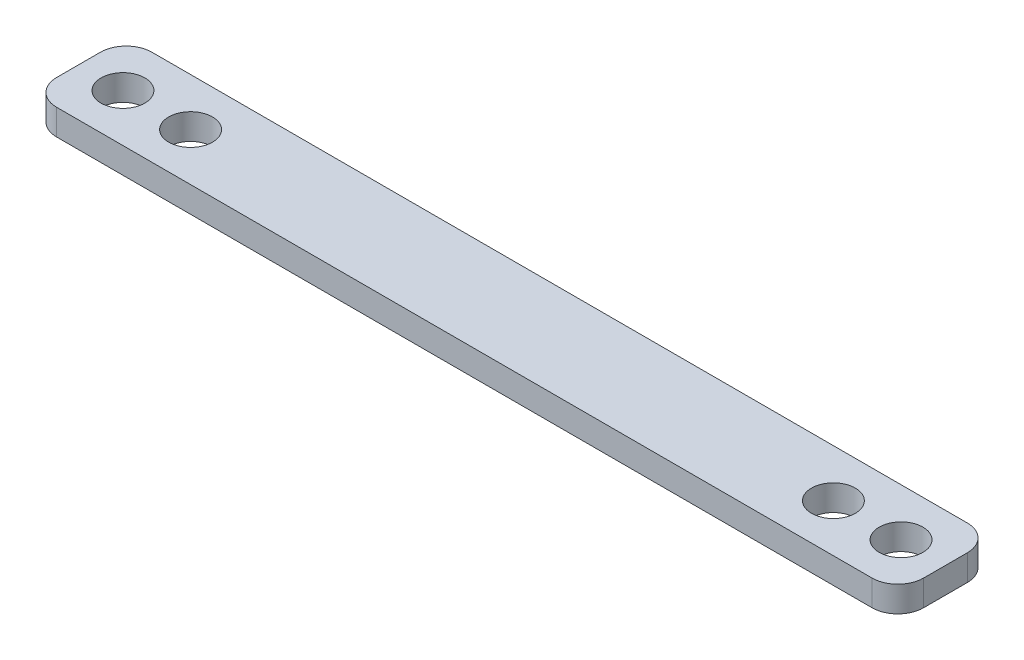
SolidWorks part; units mm, degrees
ref_plane "前视基准面" through (0, 0, 0) normal (0, 0, 1) x (1, 0, 0)
ref_plane "上视基准面" through (0, 0, 0) normal (0, 1, 0) x (1, 0, 0)
ref_plane "右视基准面" through (0, 0, 0) normal (1, 0, 0) x (0, 0, -1)
other "Configuration Table"
sketch "草图1" plane through (0, 0, 0) normal (0, 1, 0) x (1, 0, 0)
  line L0 (0.1939, -0.2441) -> (0.1939, 8.5567) construction
  line L5 (0.1939, 1.1668) -> (-30.0061, 1.1668)
  line L6 (33.8439, 4.8668) -> (-33.4561, 4.8668)
  line L8 (33.8439, 4.8668) -> (33.8439, -2.5332)
  line L9 (33.8439, -2.5332) -> (-33.4561, -2.5332)
  line L10 (-33.4561, 4.8668) -> (-33.4561, -2.5332)
  line L11 (33.8439, 4.8668) -> (-33.4561, -2.5332) construction
  line L12 (33.8439, -2.5332) -> (-33.4561, 4.8668) construction
  circle A2 centre (-24.7561, 1.1668) radius 1.7
  circle A3 centre (25.1439, 1.1668) radius 1.7
  circle A4 centre (-30.0061, 1.1668) radius 1.7
  circle A5 centre (30.3939, 1.1668) radius 1.7
  point P0 (0, 0)
  point P1 (0.1939, 1.1668)
  point P11 (0.1939, 1.1668)
  dimension "D2" = 30.2
  dimension "D5" = 33.65
  dimension "D1" = 24.95
  dimension "D3" = 67.3
  dimension "D4" = 7.4
extrude "凸台-拉伸1" add sketch "草图1" along normal blind 2
fillet "圆角1" radius 2 4 edges at (33.8439, 1, -4.8668) (33.8439, 1, 2.5332) (-33.4561, 1, -4.8668) (-33.4561, 1, 2.5332)
